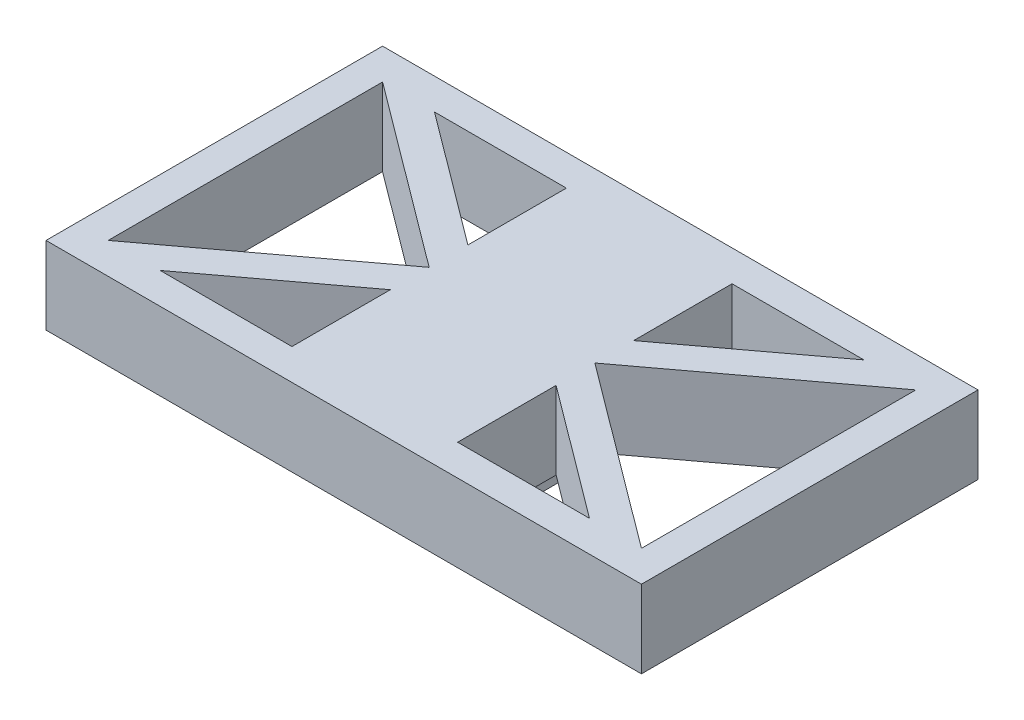
SolidWorks part; units mm, degrees
ref_plane "Front Plane" through (0, 0, 0) normal (0, 0, 1) x (1, 0, 0)
ref_plane "Top Plane" through (0, 0, 0) normal (0, 1, 0) x (1, 0, 0)
ref_plane "Right Plane" through (0, 0, 0) normal (1, 0, 0) x (0, 0, -1)
sketch "Sketch1" plane through (0, 0, 0) normal (0, 1, 0) x (1, 0, 0)
  line L1 (29.21, -16.51) -> (-29.21, -16.51)
  line L2 (29.21, -16.51) -> (29.21, 16.51)
  line L3 (29.21, 16.51) -> (-29.21, 16.51)
  line L4 (-29.21, -16.51) -> (-29.21, 16.51)
  line L5 (29.21, -16.51) -> (-29.21, 16.51) construction
  line L6 (29.21, 16.51) -> (-29.21, -16.51) construction
  point P0 (0, 0)
  dimension "D1" = 33.02
  dimension "D2" = 58.42
extrude "Boss-Extrude1" add sketch "Sketch1" along normal blind 7.62
sketch "Sketch2" plane through (0, 0, 0) normal (0, -1, 0) x (1, 0, 0)
  line L1 (5.08, -2.9329) -> (5.08, 2.9329)
  line L2 (5.08, 2.9329) -> (0, 5.8659)
  line L3 (0, 5.8659) -> (-5.08, 2.9329)
  line L4 (-5.08, 2.9329) -> (-5.08, -2.9329)
  line L5 (-5.08, -2.9329) -> (0, -5.8659)
  line L6 (0, -5.8659) -> (5.08, -2.9329)
  circle A0 centre (0, 0) radius 5.08 construction
  point P1 (0, 0)
  dimension "D1" = 10.16
extrude "Boss-Extrude2" add sketch "Sketch2" along normal blind 3.81
sketch "Sketch3" plane through (0, 0, 0) normal (0, -1, 0) x (-1, 0, 0)
  line L0 (26.162, -13.462) -> (26.162, 13.462)
  line L1 (26.162, 13.462) -> (8.128, 0)
  line L2 (8.128, 0) -> (26.162, -13.462)
  line L3 (29.21, -16.51) -> (-29.21, -16.51) construction
  line L4 (-29.21, 16.51) -> (29.21, 16.51) construction
  line L5 (29.21, 16.51) -> (29.21, -16.51) construction
  line L6 (0, 0) -> (0, -16.51) construction
  line L7 (0, 0) -> (8.128, 0) construction
  line L8 (8.128, -13.462) -> (21.0667, -13.462)
  line L9 (8.128, -3.8036) -> (8.128, -13.462)
  line L10 (21.0667, 13.462) -> (8.128, 3.8036)
  line L11 (8.128, 3.8036) -> (8.128, 13.462)
  line L12 (8.128, 13.462) -> (21.0667, 13.462)
  line L13 (21.0667, -13.462) -> (8.128, -3.8036)
  line L14 (-21.0667, -13.462) -> (-8.128, -3.8036)
  line L15 (-8.128, 13.462) -> (-21.0667, 13.462)
  line L16 (-8.128, 3.8036) -> (-8.128, 13.462)
  line L17 (-21.0667, 13.462) -> (-8.128, 3.8036)
  line L18 (-8.128, -3.8036) -> (-8.128, -13.462)
  line L19 (-8.128, -13.462) -> (-21.0667, -13.462)
  line L20 (-8.128, 0) -> (-26.162, -13.462)
  line L21 (-26.162, 13.462) -> (-8.128, 0)
  line L22 (-26.162, -13.462) -> (-26.162, 13.462)
  dimension "D1" = 3.048
  dimension "D2" = 3.048
  dimension "D3" = 3.048
  dimension "D4" = 3.048
  dimension "D5" = 3.048
extrude "Cut-Extrude1" cut sketch "Sketch3" against normal through all
